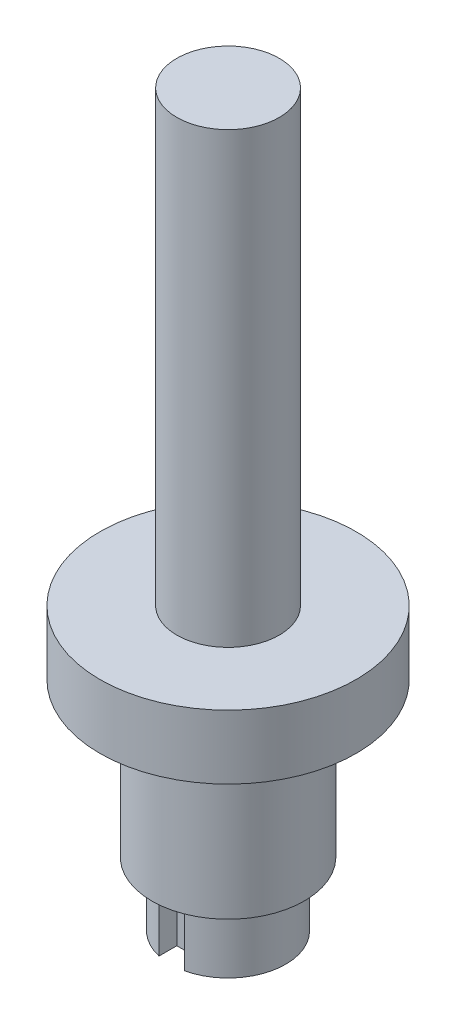
SolidWorks part; units mm, degrees
ref_plane "Front Plane" through (0, 0, 0) normal (0, 0, 1) x (1, 0, 0)
ref_plane "Top Plane" through (0, 0, 0) normal (0, 1, 0) x (1, 0, 0)
ref_plane "Right Plane" through (0, 0, 0) normal (1, 0, 0) x (0, 0, -1)
sketch "Sketch2" plane through (0, 0, 0) normal (0, 1, 0) x (1, 0, 0)
  circle A0 centre (0, 0) radius 4.5
  dimension "D1" = 9
extrude "Boss-Extrude1" add sketch "Sketch2" along normal blind 5
sketch "Sketch3" plane through (0, 5, 0) normal (0, 1, 0) x (1, 0, 0)
  circle A0 centre (0, 0) radius 5.95
  dimension "D1" = 11.9
extrude "Boss-Extrude2" add sketch "Sketch3" along normal blind 12
sketch "Sketch4" plane through (0, 17, 0) normal (0, 1, 0) x (1, 0, 0)
  circle A0 centre (0, 0) radius 10
  point P0 (0, 0)
  dimension "D1" = 20
extrude "Boss-Extrude3" add sketch "Sketch4" along normal blind 5
sketch "Sketch6" plane through (0, 0, 0) normal (0, -1, 0) x (1, 0, 0)
  circle A0 centre (0, 0) radius 1
  dimension "D1" = 2
sketch "Sketch7" plane through (0, 0, 0) normal (0, -1, 0) x (-1, 0, 0)
  point P0 (0, 0)
hole_wizard "M3 Tapped Hole1" positions "Sketch7" profile "Sketch9" tap size "M3" standard "ISO" end condition through all
cosmetic thread "Hole Thread1" parameters "D2"=3
sketch "Sketch9" plane through (0, 0, 0) normal (1, 0, 0) x (0, 0, -1)
  line L0 (0, 0) -> (0, 22)
  line L1 (0, 22) -> (1.25, 22)
  line L2 (1.25, 22) -> (1.25, 0.275)
  line L3 (1.25, 0.275) -> (1.525, 0)
  line L5 (1.525, 0) -> (0, 0)
  line L6 (-1.25, 0.275) -> (-1.525, 0) construction
  line L11 (0, -6.35) -> (0, 107.95) construction
  dimension "Thru Tap Drill Dia." = 2.5
  dimension "Thru Tap Drill Depth" = 22
  dimension "Near C'Sink Dia." = 3.05
  dimension "Near C'Sink Angle" = 90
sketch "Sketch10" plane through (0, 17, 0) normal (0, -1, 0) x (1, 0, 0)
  circle A0 centre (0, 0) radius 6
  dimension "D1" = 12
extrude "Boss-Extrude4" [suppressed] add sketch "Sketch10" along normal blind 5
sketch "Sketch11" plane through (0, 0, 0) normal (0, -1, 0) x (1, 0, 0)
  line L1 (-1, 6) -> (1, 6)
  line L2 (-1, 6) -> (-1, 3)
  line L3 (-1, 3) -> (1, 3)
  line L4 (1, 6) -> (1, 3)
  line L5 (-1, 6) -> (1, 3) construction
  line L6 (-1, 3) -> (1, 6) construction
  circle A2 centre (0, 0) radius 4.5 construction
  point P0 (0, 4.5)
  dimension "D1" = 2
  dimension "D2" = 1.5
extrude "Cut-Extrude2" cut sketch "Sketch11" against normal up to surface (5 mm away) up to face at (0, 5, 4.5)
sketch "Sketch12" plane through (0, 22, 0) normal (0, 1, 0) x (1, 0, 0)
  circle A0 centre (0, 0) radius 4
  dimension "D1" = 8
extrude "Boss-Extrude5" add sketch "Sketch12" along normal blind 35
